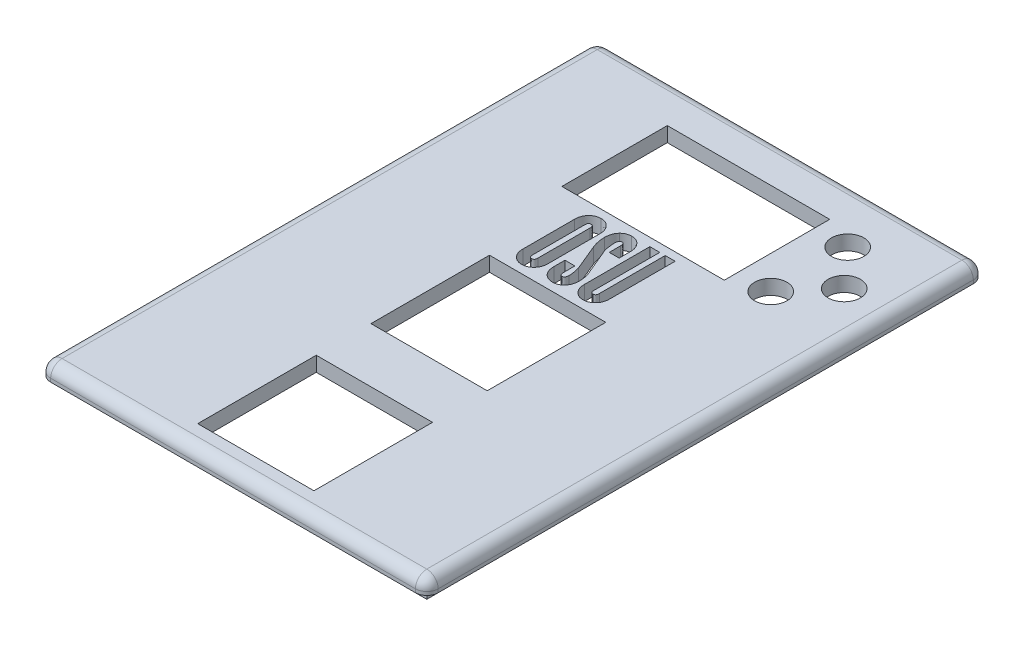
SolidWorks part; units mm, degrees
material "ABS"
ref_plane "Front Plane" through (0, 0, 0) normal (0, 0, 1) x (1, 0, 0)
ref_plane "Top Plane" through (0, 0, 0) normal (0, 1, 0) x (1, 0, 0)
ref_plane "Right Plane" through (0, 0, 0) normal (1, 0, 0) x (0, 0, -1)
sketch "Sketch1" plane through (0, 0, 0) normal (0, 1, 0) x (1, 0, 0)
  line L1 (0, 0) -> (86.36, 0)
  line L2 (0, 0) -> (0, 124.333)
  line L3 (0, 124.333) -> (86.36, 124.333)
  line L4 (86.36, 0) -> (86.36, 124.333)
extrude "Boss-Extrude1" add sketch "Sketch1" along normal blind 3.302
sketch "Sketch2" plane through (0, 0, 0) normal (0, -1, 0) x (1, 0, 0)
  line L1 (2.54, -2.54) -> (83.82, -2.54)
  line L2 (2.54, -2.54) -> (2.54, -121.793)
  line L3 (2.54, -121.793) -> (83.82, -121.793)
  line L4 (83.82, -2.54) -> (83.82, -121.793)
extrude "Boss-Extrude2" add sketch "Sketch2" along normal blind 2.54
sketch "Sketch4" plane through (0, -2.54, 0) normal (0, -1, 0) x (1, 0, 0)
  line L2 (2.54, -121.793) -> (83.82, -121.793) construction
  line L3 (63.5, -121.793) -> (63.5, -119.253)
  line L4 (81.28, -119.253) -> (81.28, -5.08)
  line L5 (63.5, -119.253) -> (81.28, -119.253)
  line L6 (5.08, -119.253) -> (5.08, -5.08)
  line L7 (22.86, -121.793) -> (63.5, -121.793)
  line L8 (81.28, -5.08) -> (63.5, -5.08)
  line L9 (22.86, -2.54) -> (63.5, -2.54)
  line L10 (63.5, -5.08) -> (63.5, -2.54)
  line L11 (83.82, -2.54) -> (2.54, -2.54) construction
  line L12 (22.86, -2.54) -> (22.86, -5.08)
  line L13 (22.86, -5.08) -> (5.08, -5.08)
  line L14 (5.08, -119.253) -> (22.86, -119.253)
  line L15 (22.86, -119.253) -> (22.86, -121.793)
extrude "Cut-Extrude1" cut sketch "Sketch4" against normal blind 2.54
sketch "Sketch6" plane through (0, 3.302, 0) normal (0, 1, 0) x (1, 0, 0)
  line L1 (30.226, 5.08) -> (56.134, 5.08)
  line L2 (30.226, 5.08) -> (30.226, 31.496)
  line L3 (30.226, 31.496) -> (56.134, 31.496)
  line L4 (56.134, 5.08) -> (56.134, 31.496)
  line L5 (30.226, 43.688) -> (56.134, 43.688)
  line L6 (30.226, 43.688) -> (30.226, 70.104)
  line L7 (30.226, 70.104) -> (56.134, 70.104)
  line L8 (56.134, 43.688) -> (56.134, 70.104)
  line L9 (25.019, 114.935) -> (61.214, 114.935)
  line L10 (25.019, 114.935) -> (25.019, 91.44)
  line L11 (25.019, 91.44) -> (61.214, 91.44)
  line L12 (61.214, 114.935) -> (61.214, 91.44)
extrude "Cut-Extrude2" cut sketch "Sketch6" against normal blind 3.302
fillet "Fillet1" radius 2.54 8 edges at (86.36, 3.302, -62.1665) (43.18, 3.302, 0) (43.18, 3.302, -124.333) (0, 3.302, -62.1665) (0, 1.651, -124.333) (0, 1.651, 0) (86.36, 1.651, 0) (86.36, 1.651, -124.333)
sketch "Sketch7" plane through (0, 3.302, 0) normal (0, 1, 0) x (1, 0, 0)
  circle A0 centre (68.58, 111.5789) radius 3.6
  circle A1 centre (76.2, 103.1875) radius 3.6
  circle A2 centre (68.58, 94.4339) radius 3.6
extrude "Cut-Extrude3" cut sketch "Sketch7" against normal through all
sketch "Sketch8" plane through (0, 3.302, 0) normal (0, 1, 0) x (1, 0, 0)
  text T0 "OSU" font "Cactus" height in points 48
extrude "Cut-Extrude4" cut sketch "Sketch8" against normal through all
